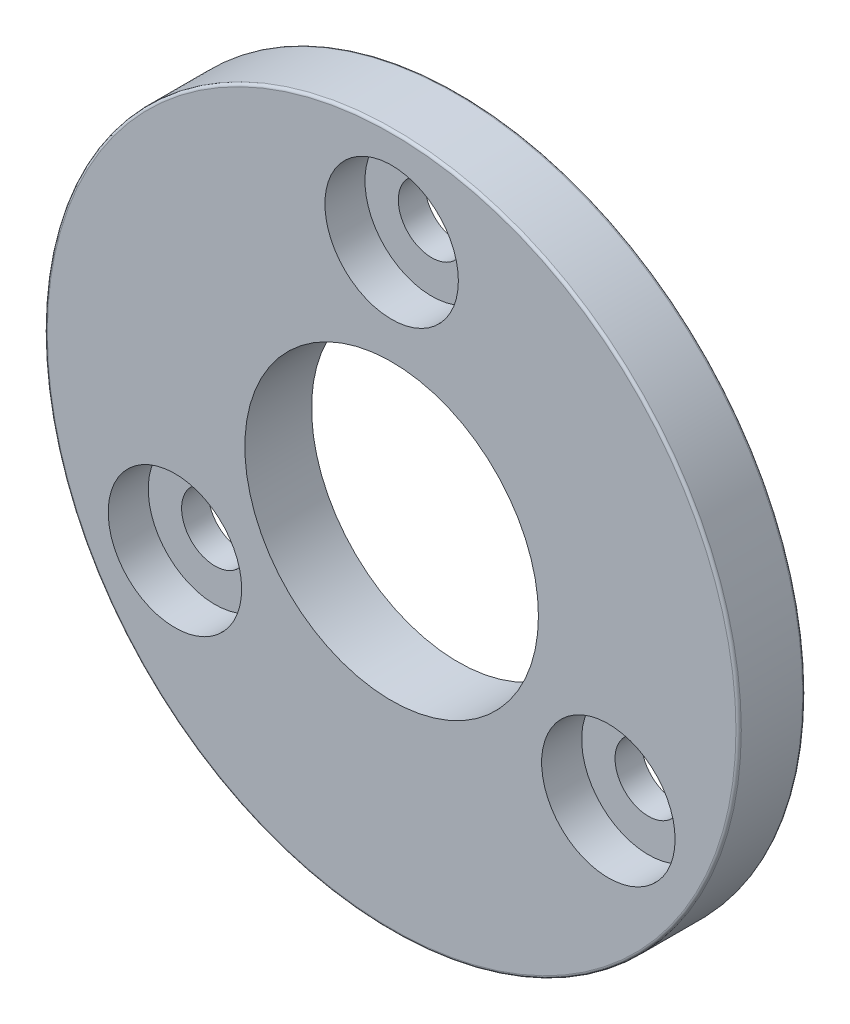
SolidWorks part; units mm, degrees
ref_plane "Front Plane" through (0, 0, 0) normal (0, 0, 1) x (1, 0, 0)
ref_plane "Top Plane" through (0, 0, 0) normal (0, 1, 0) x (1, 0, 0)
ref_plane "Right Plane" through (0, 0, 0) normal (1, 0, 0) x (0, 0, -1)
sketch "Sketch1" plane through (0, 0, 0) normal (0, 0, 1) x (1, 0, 0)
  circle A0 centre (0, 0) radius 26
  dimension "D1" = 52
extrude "Boss-Extrude1" add sketch "Sketch1" along normal blind 5
sketch "Sketch2" plane through (0, 0, 5) normal (0, 0, 1) x (1, 0, 0)
  line L0 (0, 0) -> (0, 18.75)
  circle A0 centre (0, 0) radius 18.75
  point P4 (0, 18.75)
  dimension "D1" = 37.5
hole_wizard "M5 Clearance Hole1" positions "Sketch2" profile "Sketch3" hole size "M5" standard "ISO" end condition through all
sketch "Sketch3" plane through (0, 18.75, 5) normal (1, 0, 0) x (0, -1, 0)
  line L0 (0, 0) -> (0, 5)
  line L1 (0, 5) -> (2.5, 5)
  line L2 (2.5, 5) -> (2.5, 0)
  line L5 (2.5, 0) -> (0, 0)
  line L11 (0, -6.35) -> (0, 107.95) construction
  dimension "Thru Hole Dia." = 5
  dimension "Thru Hole Depth" = 5
pattern_circular "CirPattern1" count 3 over 360 about axis through (0, 0, 0) along (0, 0, 1) of "M5 Clearance Hole1"
sketch "Sketch4" plane through (0, 0, 5) normal (0, 0, 1) x (1, 0, 0)
  circle A0 centre (0, 0) radius 11
  dimension "D1" = 22
extrude "Cut-Extrude1" cut sketch "Sketch4" against normal blind 5
fillet "Fillet1" radius 0.2 2 edges at (26, 0, 0) (26, 0, 5)
sketch "Sketch5" plane through (0, 0, 5) normal (0, 0, 1) x (1, 0, 0)
  circle A0 centre (0, 18.75) radius 5
  circle A1 centre (-16.238, -9.375) radius 5
  circle A2 centre (16.238, -9.375) radius 5
  dimension "D1" = 10
  dimension "D2" = 10
  dimension "D3" = 10
extrude "Cut-Extrude2" cut sketch "Sketch5" against normal blind 3
